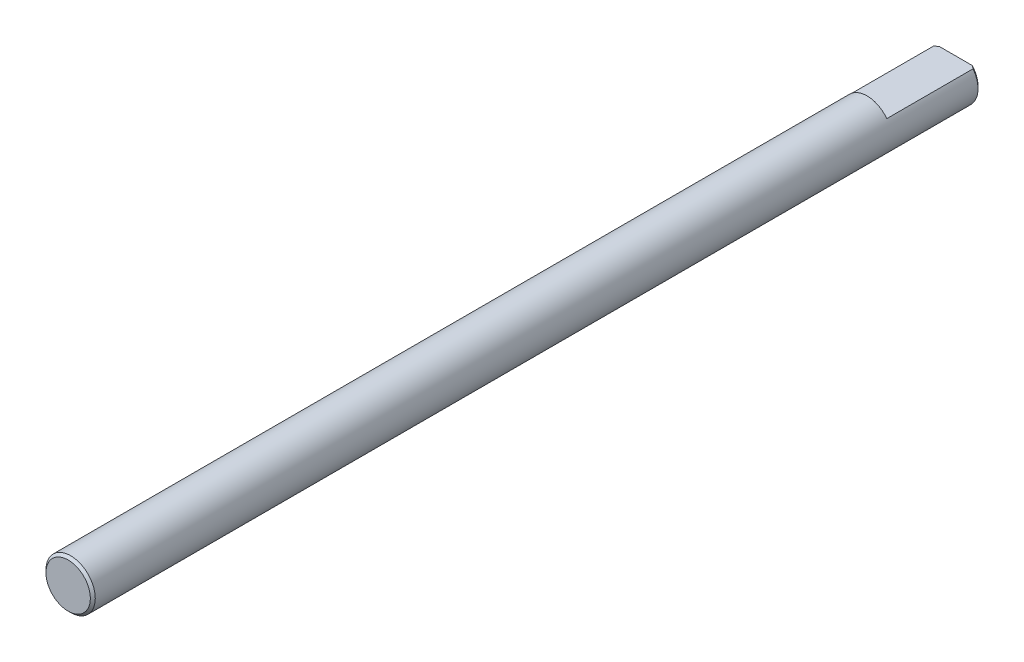
SolidWorks part; units mm, degrees
ref_plane "Front Plane" through (0, 0, 0) normal (0, 0, 1) x (1, 0, 0)
ref_plane "Top Plane" through (0, 0, 0) normal (0, 1, 0) x (1, 0, 0)
ref_plane "Right Plane" through (0, 0, 0) normal (1, 0, 0) x (0, 0, -1)
sketch "Sketch1" plane through (0, 0, 0) normal (0, 0, 1) x (1, 0, 0)
  circle A0 centre (0, 0) radius 2.5
  dimension "D1" = 5
extrude "Boss-Extrude1" add sketch "Sketch1" against normal blind 90
chamfer "Chamfer1" distance 0.25 angle 45 2 edges at (2.5, 0, 0) (2.5, 0, -90)
sketch "Sketch2" plane through (0, 0, -90) normal (0, 0, -1) x (-1, 0, 0)
  line L0 (-2, 1.5) -> (2, 1.5)
  circle A0 centre (0, 0) radius 2.5 construction
  arc A1 (2, 1.5) -> (-2, 1.5) centre (0, 0) ccw
  dimension "D1" = 1.5
extrude "Cut-Extrude1" cut sketch "Sketch2" against normal blind 9
